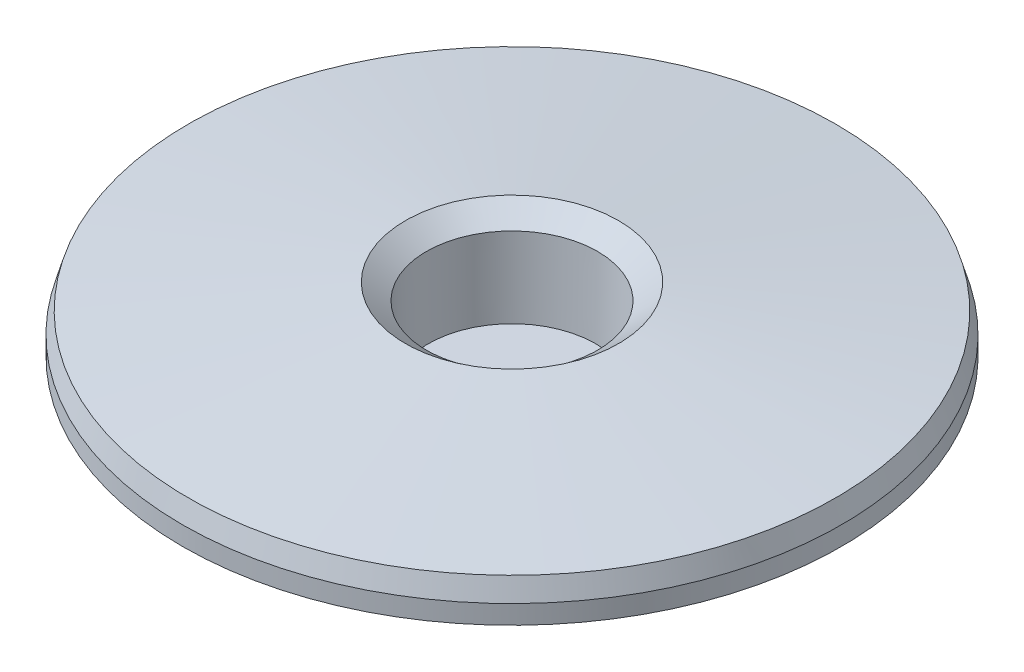
SolidWorks part; units mm, degrees
ref_plane "Front Plane" through (0, 0, 0) normal (0, 0, 1) x (1, 0, 0)
ref_plane "Top Plane" through (0, 0, 0) normal (0, 1, 0) x (1, 0, 0)
ref_plane "Right Plane" through (0, 0, 0) normal (1, 0, 0) x (0, 0, -1)
sketch "Sketch1" plane through (0, 0, 0) normal (1, 0, 0) x (0, 0, -1)
  line L0 (182.4556, 772.0394) -> (210.6938, 772.0394)
  line L1 (210.6938, 772.0394) -> (211.3387, 798.6926)
  line L2 (211.3387, 798.6926) -> (218.4169, 804.1612)
  line L3 (218.4169, 804.1612) -> (291.6812, 795.7276)
  line L4 (291.6812, 795.7276) -> (293.6436, 788.8496)
  line L5 (293.6436, 788.8496) -> (293.6436, 782.4996)
  line L6 (293.6436, 782.4996) -> (217.5108, 791.2633)
  line L7 (217.5108, 791.2633) -> (216.892, 765.6893)
  line L8 (216.892, 765.6893) -> (182.4556, 765.6893)
  line L9 (182.4556, 765.6893) -> (182.4556, 772.0394)
  dimension "D1" = 6.35
  dimension "D2" = 6.35
  dimension "D3" = 6.35
revolve "Revolve1" add sketch "Sketch1" angle 360 about L9
